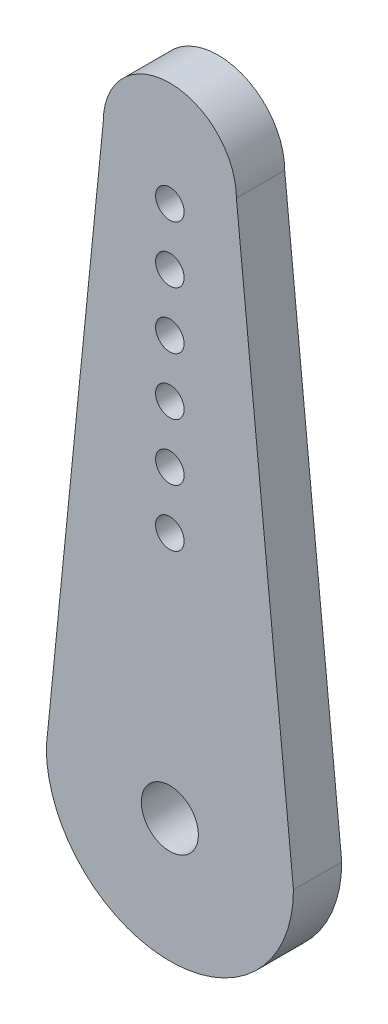
SolidWorks part; units mm, degrees
ref_plane "Plan de face" through (0, 0, 0) normal (0, 0, 1) x (1, 0, 0)
ref_plane "Plan de dessus" through (0, 0, 0) normal (0, 1, 0) x (1, 0, 0)
ref_plane "Plan de droite" through (0, 0, 0) normal (1, 0, 0) x (0, 0, -1)
sketch "Esquisse1" plane through (0, 0, 0) normal (0, 0, 1) x (1, 0, 0)
  line L0 (0, 0) -> (0, 30) construction
  line L1 (0, 0) -> (-6.5, 0) construction
  line L2 (0, 30) -> (-3.5, 30) construction
  line L3 (-3.5, 30) -> (-6.5, 0)
  line L4 (0, 30) -> (0, 33.5) construction
  line L5 (0, -6.5) -> (0, 0) construction
  line L6 (3.5, 30) -> (6.5, 0)
  circle A0 centre (0, 0) radius 1.5
  circle A1 centre (0, 13) radius 0.75
  circle A2 centre (0, 16) radius 0.75
  circle A3 centre (0, 19) radius 0.75
  circle A4 centre (0, 22) radius 0.75
  circle A5 centre (0, 25) radius 0.75
  circle A6 centre (0, 28) radius 0.75
  arc A7 (-3.5, 30) -> (3.5, 30) centre (0, 30) cw
  arc A8 (-6.5, 0) -> (6.5, 0) centre (0, 0) ccw
  dimension "D1" = 3
  dimension "D2" = 1.5
  dimension "D3" = 13
  dimension "D5" = 3
  dimension "D6" = 7
  dimension "D7" = 13
  dimension "D8" = 30
  dimension "D4" = 6
extrude "Boss.-Extru.1" add sketch "Esquisse1" along normal blind 2.54
